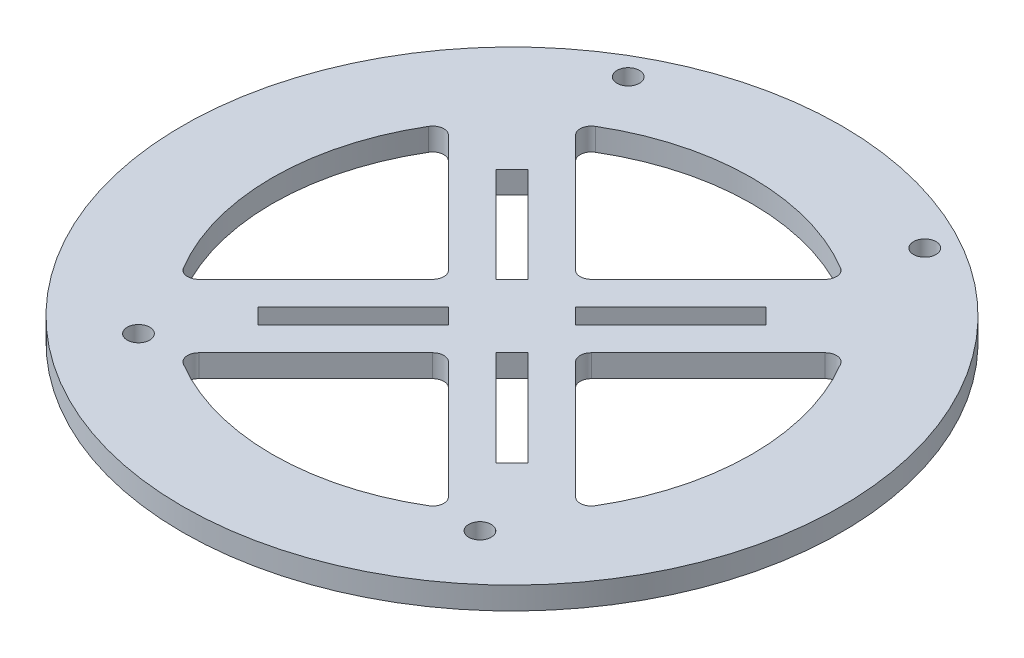
SolidWorks part; units mm, degrees
material "Teak"
ref_plane "Front Plane" through (0, 0, 0) normal (0, 0, 1) x (1, 0, 0)
ref_plane "Top Plane" through (0, 0, 0) normal (0, 1, 0) x (1, 0, 0)
ref_plane "Right Plane" through (0, 0, 0) normal (1, 0, 0) x (0, 0, -1)
sketch "Sketch1" plane through (0, 0, 0) normal (0, 1, 0) x (1, 0, 0)
  line L0 (-1.1225, -10.1028) -> (-17.6406, -26.6208)
  line L1 (17.6406, -26.6208) -> (1.1225, -10.1028)
  line L2 (-10.1028, 1.1225) -> (-26.6208, 17.6406)
  line L3 (-26.6208, -17.6406) -> (-10.1028, -1.1225)
  line L4 (1.1225, 10.1028) -> (17.6406, 26.6208)
  line L5 (-17.6406, 26.6208) -> (-1.1225, 10.1028)
  line L6 (26.6208, 17.6406) -> (10.1028, 1.1225)
  line L7 (10.1028, -1.1225) -> (26.6208, -17.6406)
  line L8 (-19.083, -16.838) -> (-16.838, -19.083)
  line L9 (-5.6127, -3.3676) -> (-3.3676, -5.6127)
  line L10 (-5.6127, -3.3676) -> (-19.083, -16.838)
  line L11 (-3.3676, -5.6127) -> (-16.838, -19.083)
  line L12 (16.838, -19.083) -> (19.083, -16.838)
  line L13 (3.3676, -5.6127) -> (5.6127, -3.3676)
  line L14 (3.3676, -5.6127) -> (16.838, -19.083)
  line L15 (5.6127, -3.3676) -> (19.083, -16.838)
  line L16 (19.083, 16.838) -> (16.838, 19.083)
  line L17 (5.6127, 3.3676) -> (3.3676, 5.6127)
  line L18 (5.6127, 3.3676) -> (19.083, 16.838)
  line L19 (3.3676, 5.6127) -> (16.838, 19.083)
  line L20 (-16.838, 19.083) -> (-19.083, 16.838)
  line L21 (-3.3676, 5.6127) -> (-5.6127, 3.3676)
  line L22 (-3.3676, 5.6127) -> (-16.838, 19.083)
  line L23 (-5.6127, 3.3676) -> (-19.083, 16.838)
  circle A0 centre (24.0227, -28.5523) radius 1.5875
  circle A1 centre (-24.2373, -28.5523) radius 1.5875
  arc A2 (1.1225, -10.1028) -> (-1.1225, -10.1028) centre (0, -11.2253) ccw
  arc A3 (17.3302, -29.1074) -> (17.6406, -26.6208) centre (16.5181, -27.7434) ccw
  arc A4 (-17.3302, -29.1074) -> (17.3302, -29.1074) centre (0, 0) ccw
  arc A5 (-17.6406, -26.6208) -> (-17.3302, -29.1074) centre (-16.5181, -27.7434) ccw
  arc A6 (-29.1074, 17.3302) -> (-29.1074, -17.3302) centre (0, 0) ccw
  arc A7 (-26.6208, 17.6406) -> (-29.1074, 17.3302) centre (-27.7434, 16.5181) ccw
  arc A8 (-10.1028, -1.1225) -> (-10.1028, 1.1225) centre (-11.2253, 0) ccw
  arc A9 (-29.1074, -17.3302) -> (-26.6208, -17.6406) centre (-27.7434, -16.5181) ccw
  arc A10 (17.3302, 29.1074) -> (-17.3302, 29.1074) centre (0, 0) ccw
  arc A11 (17.6406, 26.6208) -> (17.3302, 29.1074) centre (16.5181, 27.7434) ccw
  arc A12 (-1.1225, 10.1028) -> (1.1225, 10.1028) centre (0, 11.2253) ccw
  arc A13 (-17.3302, 29.1074) -> (-17.6406, 26.6208) centre (-16.5181, 27.7434) ccw
  arc A14 (29.1074, 17.3302) -> (26.6208, 17.6406) centre (27.7434, 16.5181) ccw
  arc A15 (29.1074, -17.3302) -> (29.1074, 17.3302) centre (0, 0) ccw
  arc A16 (26.6208, -17.6406) -> (29.1074, -17.3302) centre (27.7434, -16.5181) ccw
  arc A17 (10.1028, 1.1225) -> (10.1028, -1.1225) centre (11.2253, 0) ccw
  circle A18 centre (-21.0623, 37.4877) radius 1.5875
  circle A19 centre (20.8477, 37.4877) radius 1.5875
  circle A20 centre (0, 0) radius 46.5759
extrude "Boss-Extrude1" add sketch "Sketch1" along normal blind 3.175
